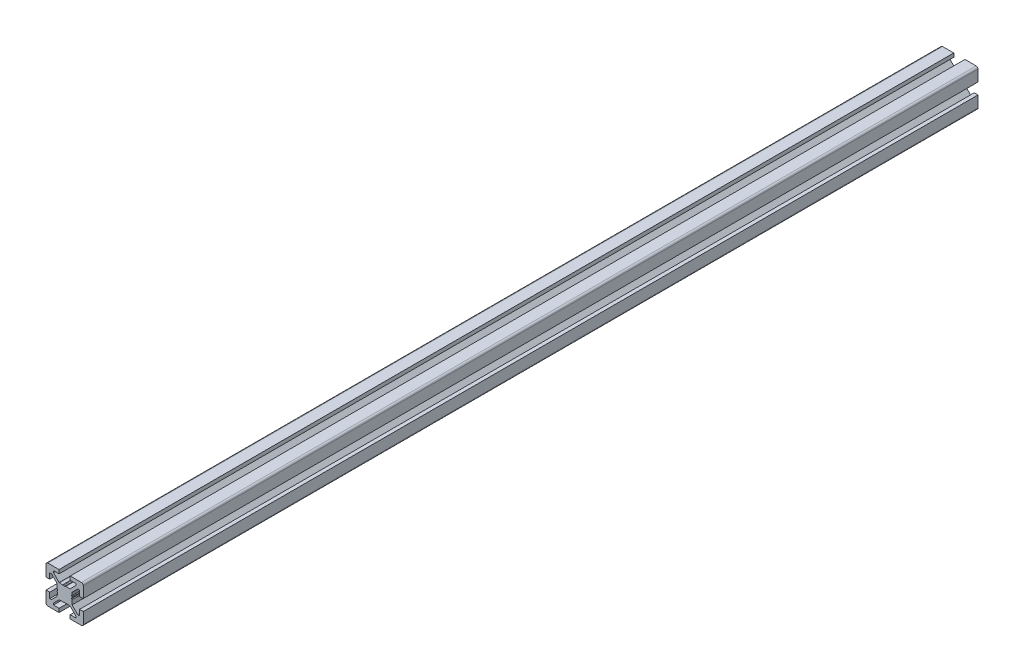
SolidWorks part; units mm, degrees
ref_plane "Front Plane" through (0, 0, 0) normal (0, 0, 1) x (1, 0, 0)
ref_plane "Top Plane" through (0, 0, 0) normal (0, 1, 0) x (1, 0, 0)
ref_plane "Right Plane" through (0, 0, 0) normal (1, 0, 0) x (0, 0, -1)
ref_plane "Plane1" through (0, 0, -2000) normal (0, 0, -1) x (-1, 0, 0)
sketch "Sketch1" plane through (0, 0, -2000) normal (0, 0, -1) x (-1, 0, 0)
  line L0 (10, -3) -> (8, -3)
  line L1 (8, -3) -> (8, -6)
  line L2 (8, -6) -> (7.0607, -6)
  line L3 (7.0607, -6) -> (4, -2.9393)
  line L4 (4, -2.9393) -> (4, -2.5)
  line L5 (4, -2.5) -> (3.751, -1.2189)
  line L6 (3.751, -1.2189) -> (3.933, -0.9036)
  line L7 (3.933, -0.4036) -> (3.7, 0)
  line L8 (3.7, 0) -> (3.933, 0.4036)
  line L9 (4, 0.6536) -> (4, 2.9393)
  line L10 (4, 2.9393) -> (7.0607, 6)
  line L11 (7.0607, 6) -> (8, 6)
  line L12 (8, 6) -> (8, 3)
  line L13 (8, 3) -> (10, 3)
  line L14 (10, 3) -> (10, 9)
  line L15 (9, 10) -> (3, 10)
  line L16 (3, 10) -> (3, 8)
  line L17 (3, 8) -> (6, 8)
  line L18 (6, 8) -> (6, 7.0607)
  line L19 (6, 7.0607) -> (2.9393, 4)
  line L20 (2.9393, 4) -> (2.5, 4)
  line L21 (2.5, 4) -> (1.2189, 3.751)
  line L22 (1.2189, 3.751) -> (0.9036, 3.933)
  line L23 (0.4036, 3.933) -> (0, 3.7)
  line L24 (0, 3.7) -> (-0.4036, 3.933)
  line L25 (-0.6536, 4) -> (-2.9393, 4)
  line L26 (-2.9393, 4) -> (-6, 7.0607)
  line L27 (-6, 7.0607) -> (-6, 8)
  line L28 (-6, 8) -> (-3, 8)
  line L29 (-3, 8) -> (-3, 10)
  line L30 (-3, 10) -> (-9, 10)
  line L31 (-10, 9) -> (-10, 3)
  line L32 (-10, 3) -> (-8, 3)
  line L33 (-8, 3) -> (-8, 6)
  line L34 (-8, 6) -> (-7.0607, 6)
  line L35 (-7.0607, 6) -> (-4, 2.9393)
  line L36 (-4, 2.9393) -> (-4, 2.5)
  line L37 (-4, 2.5) -> (-3.751, 1.2189)
  line L38 (-3.751, 1.2189) -> (-3.933, 0.9036)
  line L39 (-3.933, 0.4036) -> (-3.7, 0)
  line L40 (-3.7, 0) -> (-3.933, -0.4036)
  line L41 (-4, -0.6536) -> (-4, -2.9393)
  line L42 (-4, -2.9393) -> (-7.0607, -6)
  line L43 (-7.0607, -6) -> (-8, -6)
  line L44 (-8, -6) -> (-8, -3)
  line L45 (-8, -3) -> (-10, -3)
  line L46 (-10, -3) -> (-10, -9)
  line L47 (-9, -10) -> (-3, -10)
  line L48 (-3, -10) -> (-3, -8)
  line L49 (-3, -8) -> (-6, -8)
  line L50 (-6, -8) -> (-6, -7.0607)
  line L51 (-6, -7.0607) -> (-2.9393, -4)
  line L52 (-2.9393, -4) -> (-2.5, -4)
  line L53 (-2.5, -4) -> (-1.2189, -3.751)
  line L54 (-1.2189, -3.751) -> (-0.9036, -3.933)
  line L55 (-0.4036, -3.933) -> (0, -3.7)
  line L56 (0, -3.7) -> (0.4036, -3.933)
  line L57 (0.6536, -4) -> (2.9393, -4)
  line L58 (2.9393, -4) -> (6, -7.0607)
  line L59 (6, -7.0607) -> (6, -8)
  line L60 (6, -8) -> (3, -8)
  line L61 (3, -8) -> (3, -10)
  line L62 (3, -10) -> (9, -10)
  line L63 (10, -9) -> (10, -3)
  circle A0 centre (0, 0) radius 2.1
  arc A1 (3.933, -0.9036) -> (3.933, -0.4036) centre (3.5, -0.6536) ccw
  arc A2 (3.933, 0.4036) -> (4, 0.6536) centre (3.5, 0.6536) ccw
  arc A3 (10, 9) -> (9, 10) centre (9, 9) ccw
  arc A4 (0.9036, 3.933) -> (0.4036, 3.933) centre (0.6536, 3.5) ccw
  arc A5 (-0.4036, 3.933) -> (-0.6536, 4) centre (-0.6536, 3.5) ccw
  arc A6 (-9, 10) -> (-10, 9) centre (-9, 9) ccw
  arc A7 (-3.933, 0.9036) -> (-3.933, 0.4036) centre (-3.5, 0.6536) ccw
  arc A8 (-3.933, -0.4036) -> (-4, -0.6536) centre (-3.5, -0.6536) ccw
  arc A9 (-10, -9) -> (-9, -10) centre (-9, -9) ccw
  arc A10 (-0.9036, -3.933) -> (-0.4036, -3.933) centre (-0.6536, -3.5) ccw
  arc A11 (0.4036, -3.933) -> (0.6536, -4) centre (0.6536, -3.5) ccw
  arc A12 (9, -10) -> (10, -9) centre (9, -9) ccw
extrude "Boss-Extrude1" add sketch "Sketch1" against normal blind 400
sketch "草图1" plane through (0, 0, -1600) normal (0, 0, 1) x (1, 0, 0)
  line L64 (-10, -3) -> (-10, -9)
  line L65 (-8, -3) -> (-10, -3)
  line L66 (-8, -6) -> (-8, -3)
  line L67 (-7.0607, -6) -> (-8, -6)
  line L68 (-4, -2.9393) -> (-7.0607, -6)
  line L69 (-4, -2.5) -> (-4, -2.9393)
  line L70 (-3.751, -1.2189) -> (-4, -2.5)
  line L71 (-3.933, -0.9036) -> (-3.751, -1.2189)
  line L72 (-3.7, 0) -> (-3.933, -0.4036)
  line L73 (-3.933, 0.4036) -> (-3.7, 0)
  line L74 (-4, 2.9393) -> (-4, 0.6536)
  line L75 (-7.0607, 6) -> (-4, 2.9393)
  line L76 (-8, 6) -> (-7.0607, 6)
  line L77 (-8, 3) -> (-8, 6)
  line L78 (-10, 3) -> (-8, 3)
  line L79 (-10, 9) -> (-10, 3)
  line L80 (-3, 10) -> (-9, 10)
  line L81 (-3, 8) -> (-3, 10)
  line L82 (-6, 8) -> (-3, 8)
  line L83 (-6, 7.0607) -> (-6, 8)
  line L84 (-2.9393, 4) -> (-6, 7.0607)
  line L85 (-2.5, 4) -> (-2.9393, 4)
  line L86 (-1.2189, 3.751) -> (-2.5, 4)
  line L87 (-0.9036, 3.933) -> (-1.2189, 3.751)
  line L88 (0, 3.7) -> (-0.4036, 3.933)
  line L89 (0.4036, 3.933) -> (0, 3.7)
  line L90 (2.9393, 4) -> (0.6536, 4)
  line L91 (6, 7.0607) -> (2.9393, 4)
  line L92 (6, 8) -> (6, 7.0607)
  line L93 (3, 8) -> (6, 8)
  line L94 (3, 10) -> (3, 8)
  line L95 (9, 10) -> (3, 10)
  line L96 (10, 3) -> (10, 9)
  line L97 (8, 3) -> (10, 3)
  line L98 (8, 6) -> (8, 3)
  line L99 (7.0607, 6) -> (8, 6)
  line L100 (4, 2.9393) -> (7.0607, 6)
  line L101 (4, 2.5) -> (4, 2.9393)
  line L102 (3.751, 1.2189) -> (4, 2.5)
  line L103 (3.933, 0.9036) -> (3.751, 1.2189)
  line L104 (3.7, 0) -> (3.933, 0.4036)
  line L105 (3.933, -0.4036) -> (3.7, 0)
  line L106 (4, -2.9393) -> (4, -0.6536)
  line L107 (7.0607, -6) -> (4, -2.9393)
  line L108 (8, -6) -> (7.0607, -6)
  line L109 (8, -3) -> (8, -6)
  line L110 (10, -3) -> (8, -3)
  line L111 (10, -9) -> (10, -3)
  line L112 (3, -10) -> (9, -10)
  line L113 (3, -8) -> (3, -10)
  line L114 (6, -8) -> (3, -8)
  line L115 (6, -7.0607) -> (6, -8)
  line L116 (2.9393, -4) -> (6, -7.0607)
  line L117 (2.5, -4) -> (2.9393, -4)
  line L118 (1.2189, -3.751) -> (2.5, -4)
  line L119 (0.9036, -3.933) -> (1.2189, -3.751)
  line L120 (0, -3.7) -> (0.4036, -3.933)
  line L121 (-0.4036, -3.933) -> (0, -3.7)
  line L122 (-2.9393, -4) -> (-0.6536, -4)
  line L123 (-6, -7.0607) -> (-2.9393, -4)
  line L124 (-6, -8) -> (-6, -7.0607)
  line L125 (-3, -8) -> (-6, -8)
  line L126 (-3, -10) -> (-3, -8)
  line L127 (-9, -10) -> (-3, -10)
  line L128 (-10, -3) -> (-10, -9)
  line L129 (-8, -3) -> (-10, -3)
  line L130 (-8, -6) -> (-8, -3)
  line L131 (-7.0607, -6) -> (-8, -6)
  line L132 (-4, -2.9393) -> (-7.0607, -6)
  line L133 (-4, -2.5) -> (-4, -2.9393)
  line L134 (-3.751, -1.2189) -> (-4, -2.5)
  line L135 (-3.933, -0.9036) -> (-3.751, -1.2189)
  line L136 (-3.7, 0) -> (-3.933, -0.4036)
  line L137 (-3.933, 0.4036) -> (-3.7, 0)
  line L138 (-4, 2.9393) -> (-4, 0.6536)
  line L139 (-7.0607, 6) -> (-4, 2.9393)
  line L140 (-8, 6) -> (-7.0607, 6)
  line L141 (-8, 3) -> (-8, 6)
  line L142 (-10, 3) -> (-8, 3)
  line L143 (-10, 9) -> (-10, 3)
  line L144 (-3, 10) -> (-9, 10)
  line L145 (-3, 8) -> (-3, 10)
  line L146 (-6, 8) -> (-3, 8)
  line L147 (-6, 7.0607) -> (-6, 8)
  line L148 (-2.9393, 4) -> (-6, 7.0607)
  line L149 (-2.5, 4) -> (-2.9393, 4)
  line L150 (-1.2189, 3.751) -> (-2.5, 4)
  line L151 (-0.9036, 3.933) -> (-1.2189, 3.751)
  line L152 (0, 3.7) -> (-0.4036, 3.933)
  line L153 (0.4036, 3.933) -> (0, 3.7)
  line L154 (2.9393, 4) -> (0.6536, 4)
  line L155 (6, 7.0607) -> (2.9393, 4)
  line L156 (6, 8) -> (6, 7.0607)
  line L157 (3, 8) -> (6, 8)
  line L158 (3, 10) -> (3, 8)
  line L159 (9, 10) -> (3, 10)
  line L160 (10, 3) -> (10, 9)
  line L161 (8, 3) -> (10, 3)
  line L162 (8, 6) -> (8, 3)
  line L163 (7.0607, 6) -> (8, 6)
  line L164 (4, 2.9393) -> (7.0607, 6)
  line L165 (4, 2.5) -> (4, 2.9393)
  line L166 (3.751, 1.2189) -> (4, 2.5)
  line L167 (3.933, 0.9036) -> (3.751, 1.2189)
  line L168 (3.7, 0) -> (3.933, 0.4036)
  line L169 (3.933, -0.4036) -> (3.7, 0)
  line L170 (4, -2.9393) -> (4, -0.6536)
  line L171 (7.0607, -6) -> (4, -2.9393)
  line L172 (8, -6) -> (7.0607, -6)
  line L173 (8, -3) -> (8, -6)
  line L174 (10, -3) -> (8, -3)
  line L175 (10, -9) -> (10, -3)
  line L176 (3, -10) -> (9, -10)
  line L177 (3, -8) -> (3, -10)
  line L178 (6, -8) -> (3, -8)
  line L179 (6, -7.0607) -> (6, -8)
  line L180 (2.9393, -4) -> (6, -7.0607)
  line L181 (2.5, -4) -> (2.9393, -4)
  line L182 (1.2189, -3.751) -> (2.5, -4)
  line L183 (0.9036, -3.933) -> (1.2189, -3.751)
  line L184 (0, -3.7) -> (0.4036, -3.933)
  line L185 (-0.4036, -3.933) -> (0, -3.7)
  line L186 (-2.9393, -4) -> (-0.6536, -4)
  line L187 (-6, -7.0607) -> (-2.9393, -4)
  line L188 (-6, -8) -> (-6, -7.0607)
  line L189 (-3, -8) -> (-6, -8)
  line L190 (-3, -10) -> (-3, -8)
  line L191 (-9, -10) -> (-3, -10)
  arc A12 (-3.933, -0.4036) -> (-3.933, -0.9036) centre (-3.5, -0.6536) ccw
  arc A13 (-4, 0.6536) -> (-3.933, 0.4036) centre (-3.5, 0.6536) ccw
  arc A14 (-9, 10) -> (-10, 9) centre (-9, 9) ccw
  arc A15 (-0.4036, 3.933) -> (-0.9036, 3.933) centre (-0.6536, 3.5) ccw
  arc A16 (0.6536, 4) -> (0.4036, 3.933) centre (0.6536, 3.5) ccw
  arc A17 (10, 9) -> (9, 10) centre (9, 9) ccw
  arc A18 (3.933, 0.4036) -> (3.933, 0.9036) centre (3.5, 0.6536) ccw
  arc A19 (4, -0.6536) -> (3.933, -0.4036) centre (3.5, -0.6536) ccw
  arc A20 (9, -10) -> (10, -9) centre (9, -9) ccw
  arc A21 (0.4036, -3.933) -> (0.9036, -3.933) centre (0.6536, -3.5) ccw
  arc A22 (-0.6536, -4) -> (-0.4036, -3.933) centre (-0.6536, -3.5) ccw
  arc A23 (-10, -9) -> (-9, -10) centre (-9, -9) ccw
  arc A24 (-3.933, -0.4036) -> (-3.933, -0.9036) centre (-3.5, -0.6536) ccw
  arc A25 (-4, 0.6536) -> (-3.933, 0.4036) centre (-3.5, 0.6536) ccw
  arc A26 (-9, 10) -> (-10, 9) centre (-9, 9) ccw
  arc A27 (-0.4036, 3.933) -> (-0.9036, 3.933) centre (-0.6536, 3.5) ccw
  arc A28 (0.6536, 4) -> (0.4036, 3.933) centre (0.6536, 3.5) ccw
  arc A29 (10, 9) -> (9, 10) centre (9, 9) ccw
  arc A30 (3.933, 0.4036) -> (3.933, 0.9036) centre (3.5, 0.6536) ccw
  arc A31 (4, -0.6536) -> (3.933, -0.4036) centre (3.5, -0.6536) ccw
  arc A32 (9, -10) -> (10, -9) centre (9, -9) ccw
  arc A33 (0.4036, -3.933) -> (0.9036, -3.933) centre (0.6536, -3.5) ccw
  arc A34 (-0.6536, -4) -> (-0.4036, -3.933) centre (-0.6536, -3.5) ccw
  arc A35 (-10, -9) -> (-9, -10) centre (-9, -9) ccw
  dimension "D1" = 0
extrude "凸台-拉伸1" add sketch "草图1" along normal blind 20
sketch "草图2" plane through (0, 0, -1580) normal (0, 0, 1) x (1, 0, 0)
  line L64 (-9, -10) -> (-3, -10)
  line L65 (-3, -10) -> (-3, -8)
  line L66 (-3, -8) -> (-6, -8)
  line L67 (-6, -8) -> (-6, -7.0607)
  line L68 (-6, -7.0607) -> (-2.9393, -4)
  line L69 (-2.9393, -4) -> (-0.6536, -4)
  line L70 (-0.4036, -3.933) -> (0, -3.7)
  line L71 (0, -3.7) -> (0.4036, -3.933)
  line L72 (0.9036, -3.933) -> (1.2189, -3.751)
  line L73 (1.2189, -3.751) -> (2.5, -4)
  line L74 (2.5, -4) -> (2.9393, -4)
  line L75 (2.9393, -4) -> (6, -7.0607)
  line L76 (6, -7.0607) -> (6, -8)
  line L77 (6, -8) -> (3, -8)
  line L78 (3, -8) -> (3, -10)
  line L79 (3, -10) -> (9, -10)
  line L80 (10, -9) -> (10, -3)
  line L81 (10, -3) -> (8, -3)
  line L82 (8, -3) -> (8, -6)
  line L83 (8, -6) -> (7.0607, -6)
  line L84 (7.0607, -6) -> (4, -2.9393)
  line L85 (4, -2.9393) -> (4, -0.6536)
  line L86 (3.933, -0.4036) -> (3.7, 0)
  line L87 (3.7, 0) -> (3.933, 0.4036)
  line L88 (3.933, 0.9036) -> (3.751, 1.2189)
  line L89 (3.751, 1.2189) -> (4, 2.5)
  line L90 (4, 2.5) -> (4, 2.9393)
  line L91 (4, 2.9393) -> (7.0607, 6)
  line L92 (7.0607, 6) -> (8, 6)
  line L93 (8, 6) -> (8, 3)
  line L94 (8, 3) -> (10, 3)
  line L95 (10, 3) -> (10, 9)
  line L96 (9, 10) -> (3, 10)
  line L97 (3, 10) -> (3, 8)
  line L98 (3, 8) -> (6, 8)
  line L99 (6, 8) -> (6, 7.0607)
  line L100 (6, 7.0607) -> (2.9393, 4)
  line L101 (2.9393, 4) -> (0.6536, 4)
  line L102 (0.4036, 3.933) -> (0, 3.7)
  line L103 (0, 3.7) -> (-0.4036, 3.933)
  line L104 (-0.9036, 3.933) -> (-1.2189, 3.751)
  line L105 (-1.2189, 3.751) -> (-2.5, 4)
  line L106 (-2.5, 4) -> (-2.9393, 4)
  line L107 (-2.9393, 4) -> (-6, 7.0607)
  line L108 (-6, 7.0607) -> (-6, 8)
  line L109 (-6, 8) -> (-3, 8)
  line L110 (-3, 8) -> (-3, 10)
  line L111 (-3, 10) -> (-9, 10)
  line L112 (-10, 9) -> (-10, 3)
  line L113 (-10, 3) -> (-8, 3)
  line L114 (-8, 3) -> (-8, 6)
  line L115 (-8, 6) -> (-7.0607, 6)
  line L116 (-7.0607, 6) -> (-4, 2.9393)
  line L117 (-4, 2.9393) -> (-4, 0.6536)
  line L118 (-3.933, 0.4036) -> (-3.7, 0)
  line L119 (-3.7, 0) -> (-3.933, -0.4036)
  line L120 (-3.933, -0.9036) -> (-3.751, -1.2189)
  line L121 (-3.751, -1.2189) -> (-4, -2.5)
  line L122 (-4, -2.5) -> (-4, -2.9393)
  line L123 (-4, -2.9393) -> (-7.0607, -6)
  line L124 (-7.0607, -6) -> (-8, -6)
  line L125 (-8, -6) -> (-8, -3)
  line L126 (-8, -3) -> (-10, -3)
  line L127 (-10, -3) -> (-10, -9)
  line L128 (-9, -10) -> (-3, -10)
  line L129 (-3, -10) -> (-3, -8)
  line L130 (-3, -8) -> (-6, -8)
  line L131 (-6, -8) -> (-6, -7.0607)
  line L132 (-6, -7.0607) -> (-2.9393, -4)
  line L133 (-2.9393, -4) -> (-0.6536, -4)
  line L134 (-0.4036, -3.933) -> (0, -3.7)
  line L135 (0, -3.7) -> (0.4036, -3.933)
  line L136 (0.9036, -3.933) -> (1.2189, -3.751)
  line L137 (1.2189, -3.751) -> (2.5, -4)
  line L138 (2.5, -4) -> (2.9393, -4)
  line L139 (2.9393, -4) -> (6, -7.0607)
  line L140 (6, -7.0607) -> (6, -8)
  line L141 (6, -8) -> (3, -8)
  line L142 (3, -8) -> (3, -10)
  line L143 (3, -10) -> (9, -10)
  line L144 (10, -9) -> (10, -3)
  line L145 (10, -3) -> (8, -3)
  line L146 (8, -3) -> (8, -6)
  line L147 (8, -6) -> (7.0607, -6)
  line L148 (7.0607, -6) -> (4, -2.9393)
  line L149 (4, -2.9393) -> (4, -0.6536)
  line L150 (3.933, -0.4036) -> (3.7, 0)
  line L151 (3.7, 0) -> (3.933, 0.4036)
  line L152 (3.933, 0.9036) -> (3.751, 1.2189)
  line L153 (3.751, 1.2189) -> (4, 2.5)
  line L154 (4, 2.5) -> (4, 2.9393)
  line L155 (4, 2.9393) -> (7.0607, 6)
  line L156 (7.0607, 6) -> (8, 6)
  line L157 (8, 6) -> (8, 3)
  line L158 (8, 3) -> (10, 3)
  line L159 (10, 3) -> (10, 9)
  line L160 (9, 10) -> (3, 10)
  line L161 (3, 10) -> (3, 8)
  line L162 (3, 8) -> (6, 8)
  line L163 (6, 8) -> (6, 7.0607)
  line L164 (6, 7.0607) -> (2.9393, 4)
  line L165 (2.9393, 4) -> (0.6536, 4)
  line L166 (0.4036, 3.933) -> (0, 3.7)
  line L167 (0, 3.7) -> (-0.4036, 3.933)
  line L168 (-0.9036, 3.933) -> (-1.2189, 3.751)
  line L169 (-1.2189, 3.751) -> (-2.5, 4)
  line L170 (-2.5, 4) -> (-2.9393, 4)
  line L171 (-2.9393, 4) -> (-6, 7.0607)
  line L172 (-6, 7.0607) -> (-6, 8)
  line L173 (-6, 8) -> (-3, 8)
  line L174 (-3, 8) -> (-3, 10)
  line L175 (-3, 10) -> (-9, 10)
  line L176 (-10, 9) -> (-10, 3)
  line L177 (-10, 3) -> (-8, 3)
  line L178 (-8, 3) -> (-8, 6)
  line L179 (-8, 6) -> (-7.0607, 6)
  line L180 (-7.0607, 6) -> (-4, 2.9393)
  line L181 (-4, 2.9393) -> (-4, 0.6536)
  line L182 (-3.933, 0.4036) -> (-3.7, 0)
  line L183 (-3.7, 0) -> (-3.933, -0.4036)
  line L184 (-3.933, -0.9036) -> (-3.751, -1.2189)
  line L185 (-3.751, -1.2189) -> (-4, -2.5)
  line L186 (-4, -2.5) -> (-4, -2.9393)
  line L187 (-4, -2.9393) -> (-7.0607, -6)
  line L188 (-7.0607, -6) -> (-8, -6)
  line L189 (-8, -6) -> (-8, -3)
  line L190 (-8, -3) -> (-10, -3)
  line L191 (-10, -3) -> (-10, -9)
  arc A12 (-10, -9) -> (-9, -10) centre (-9, -9) ccw
  arc A13 (-0.6536, -4) -> (-0.4036, -3.933) centre (-0.6536, -3.5) ccw
  arc A14 (0.4036, -3.933) -> (0.9036, -3.933) centre (0.6536, -3.5) ccw
  arc A15 (9, -10) -> (10, -9) centre (9, -9) ccw
  arc A16 (4, -0.6536) -> (3.933, -0.4036) centre (3.5, -0.6536) ccw
  arc A17 (3.933, 0.4036) -> (3.933, 0.9036) centre (3.5, 0.6536) ccw
  arc A18 (10, 9) -> (9, 10) centre (9, 9) ccw
  arc A19 (0.6536, 4) -> (0.4036, 3.933) centre (0.6536, 3.5) ccw
  arc A20 (-0.4036, 3.933) -> (-0.9036, 3.933) centre (-0.6536, 3.5) ccw
  arc A21 (-9, 10) -> (-10, 9) centre (-9, 9) ccw
  arc A22 (-4, 0.6536) -> (-3.933, 0.4036) centre (-3.5, 0.6536) ccw
  arc A23 (-3.933, -0.4036) -> (-3.933, -0.9036) centre (-3.5, -0.6536) ccw
  arc A24 (-10, -9) -> (-9, -10) centre (-9, -9) ccw
  arc A25 (-0.6536, -4) -> (-0.4036, -3.933) centre (-0.6536, -3.5) ccw
  arc A26 (0.4036, -3.933) -> (0.9036, -3.933) centre (0.6536, -3.5) ccw
  arc A27 (9, -10) -> (10, -9) centre (9, -9) ccw
  arc A28 (4, -0.6536) -> (3.933, -0.4036) centre (3.5, -0.6536) ccw
  arc A29 (3.933, 0.4036) -> (3.933, 0.9036) centre (3.5, 0.6536) ccw
  arc A30 (10, 9) -> (9, 10) centre (9, 9) ccw
  arc A31 (0.6536, 4) -> (0.4036, 3.933) centre (0.6536, 3.5) ccw
  arc A32 (-0.4036, 3.933) -> (-0.9036, 3.933) centre (-0.6536, 3.5) ccw
  arc A33 (-9, 10) -> (-10, 9) centre (-9, 9) ccw
  arc A34 (-4, 0.6536) -> (-3.933, 0.4036) centre (-3.5, 0.6536) ccw
  arc A35 (-3.933, -0.4036) -> (-3.933, -0.9036) centre (-3.5, -0.6536) ccw
  dimension "D1" = 0
extrude "凸台-拉伸2" add sketch "草图2" along normal blind 60
